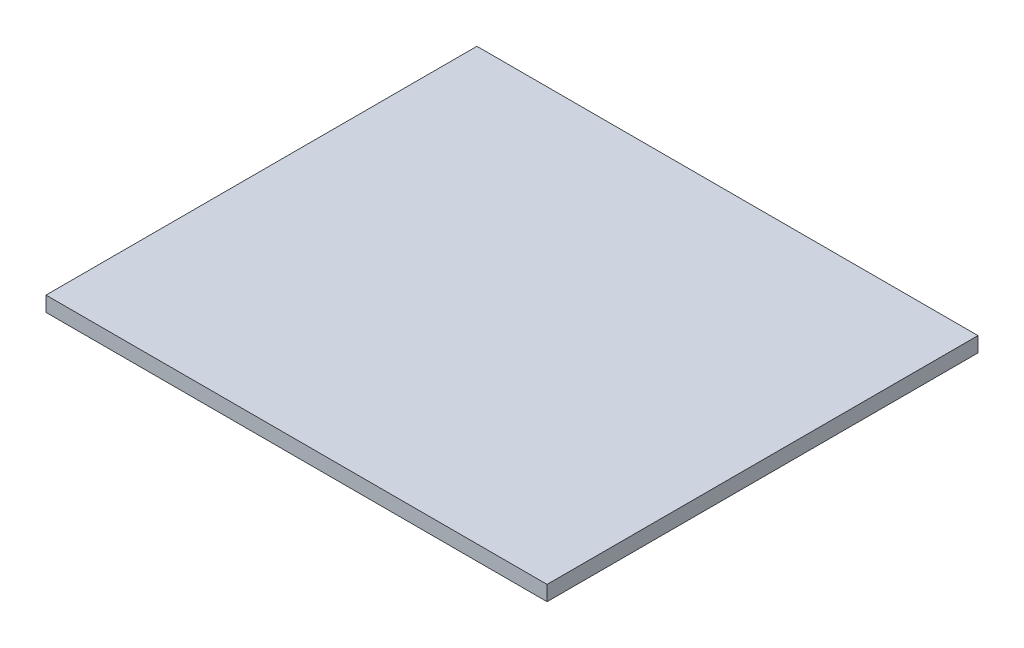
SolidWorks part; units mm, degrees
ref_plane "Front Plane" through (0, 0, 0) normal (0, 0, 1) x (1, 0, 0)
ref_plane "Top Plane" through (0, 0, 0) normal (0, 1, 0) x (1, 0, 0)
ref_plane "Right Plane" through (0, 0, 0) normal (1, 0, 0) x (0, 0, -1)
sketch "Sketch1" plane through (0, 0, 0) normal (0, 1, 0) x (1, 0, 0)
  line L1 (-50, -43) -> (50, -43)
  line L2 (-50, -43) -> (-50, 43)
  line L3 (-50, 43) -> (50, 43)
  line L4 (50, -43) -> (50, 43)
  line L5 (-50, -43) -> (50, 43) construction
  line L6 (-50, 43) -> (50, -43) construction
  point P0 (0, 0)
  dimension "D1" = 100
  dimension "D2" = 86
extrude "Boss-Extrude1" add sketch "Sketch1" along normal blind 3
